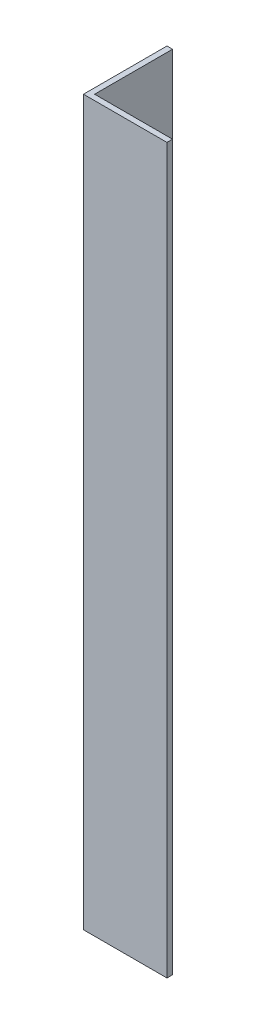
SolidWorks part; units mm, degrees
ref_plane "正面" through (0, 0, 0) normal (0, 0, 1) x (1, 0, 0)
ref_plane "平面" through (0, 0, 0) normal (0, 1, 0) x (1, 0, 0)
ref_plane "右側面" through (0, 0, 0) normal (1, 0, 0) x (0, 0, -1)
sketch "ｽｹｯﾁ1" plane through (0, 0, 0) normal (0, 1, 0) x (1, 0, 0)
  line L1 (0, 0) -> (15, 0)
  line L2 (0, 0) -> (0, -1)
  line L3 (0, -1) -> (15, -1)
  line L4 (15, 0) -> (15, -1)
  dimension "D1" = 15
  dimension "D2" = 1
sketch "ｽｹｯﾁ2" plane through (0, 0, 0) normal (0, 1, 0) x (1, 0, 0)
extrude "ﾎﾞｽ - 押し出し1" add sketch "ｽｹｯﾁ1" along normal blind 130
sketch "ｽｹｯﾁ3" plane through (0, 0, 0) normal (0, 0, -1) x (-1, 0, 0)
  line L1 (0, 130) -> (-1, 130)
  line L2 (0, 130) -> (0, 0)
  line L3 (0, 0) -> (-1, 0)
  line L4 (-1, 130) -> (-1, 0)
  dimension "D1" = 1
  dimension "D2" = 130
extrude "ﾎﾞｽ - 押し出し2" add sketch "ｽｹｯﾁ3" along normal blind 14
